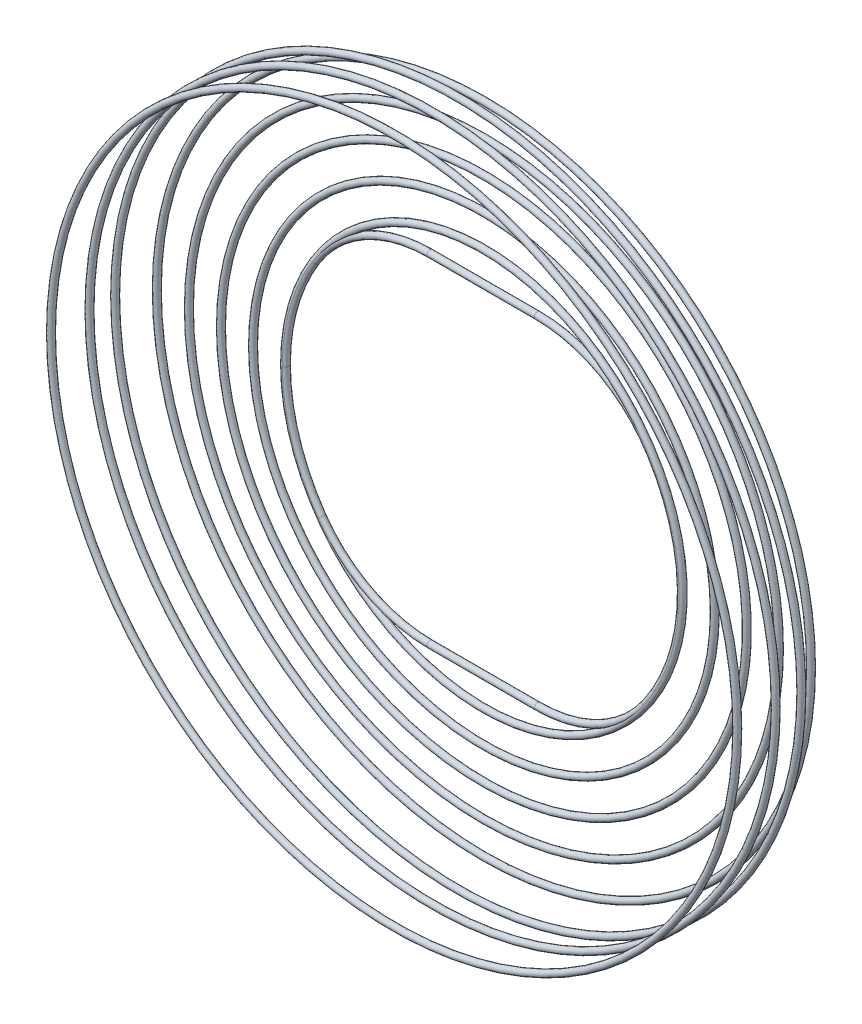
SolidWorks part; units mm, degrees
ref_plane "Спереди" through (0, 0, 0) normal (0, 0, 1) x (1, 0, 0)
ref_plane "Сверху" through (0, 0, 0) normal (0, 1, 0) x (1, 0, 0)
ref_plane "Справа" through (0, 0, 0) normal (1, 0, 0) x (0, 0, -1)
sketch "Эскиз1" plane through (0, 0, 0) normal (0, 0, 1) x (1, 0, 0)
  line L9 (-16.7402, 52.4907) -> (16.7402, 52.4907)
  line L11 (16.7402, -53.0367) -> (-16.7402, -53.0367)
  arc A25 (52.3384, 32.7834) -> (16.7402, 52.4907) centre (16.7402, 10.4856) ccw
  arc A26 (50.6128, -35.3894) -> (52.3384, 32.7834) centre (0, 0) ccw
  arc A27 (16.7402, -53.0367) -> (50.6128, -35.3894) centre (16.7402, -11.7051) ccw
  arc A28 (-16.7402, -53.0367) -> (-50.6128, -35.3894) centre (-16.7402, -11.7051) cw
  arc A29 (-52.3384, 32.7834) -> (-50.6128, -35.3894) centre (0, 0) ccw
  arc A30 (-16.7402, 52.4907) -> (-52.3384, 32.7834) centre (-16.7402, 10.4856) ccw
sketch "Эскиз2" plane through (0, 0, 0) normal (0, 1, 0) x (1, 0, 0)
  circle A0 centre (-61.7581, 0) radius 1
  dimension "D1" = 2
sketch "Эскиз4" plane through (0, 0, 0) normal (0, 1, 0) x (1, 0, 0)
  line L16 (0, 25.3938) -> (0, -26.9637) construction
  circle A2 centre (-62, 0) radius 1
  circle A3 centre (-72, 0) radius 1
  circle A4 centre (-82, 0) radius 1
  circle A5 centre (-92, 0) radius 1
  circle A6 centre (-102, 0) radius 1
  circle A8 centre (-107, -8) radius 1
  circle A9 centre (-107, -16) radius 1
  circle A10 centre (-107, -28) radius 1
  dimension "D3" = 2
  dimension "D4" = 2
  dimension "D5" = 2
  dimension "D6" = 2
  dimension "D7" = 2
  dimension "D9" = 2
  dimension "D10" = 2
  dimension "D11" = 2
  dimension "D12" = 5
  dimension "D13" = 5
  dimension "D14" = 5
  dimension "D15" = 8
  dimension "D16" = 10
  dimension "D17" = 8
  dimension "D18" = 12
revolve "Повернуть1" add sketch "Эскиз4" angle 360 about L16
sweep "По траектории1" add profiles "Эскиз2" path "Эскиз1"
